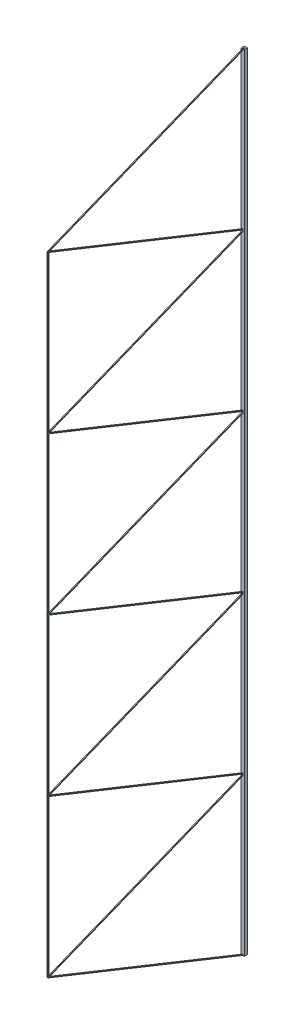
SolidWorks part; units mm, degrees
material "Alloy Steel (SS)"
ref_plane "Front Plane" through (0, 0, 0) normal (1, 0, 0) x (0, 1, 0)
ref_plane "Top Plane" through (0, 0, 0) normal (0, 0, 1) x (0, 1, 0)
ref_plane "Right Plane" through (0, 0, 0) normal (0, 1, 0) x (-1, 0, 0)
sketch "Sketch1" plane through (0, 0, 0) normal (1, 0, 0) x (0, 1, 0)
  line L0 (0, 0) -> (10000, 0)
  line L20 (9000, 2500) -> (7000, 2500)
  line L21 (7000, 2500) -> (5000, 2500)
  line L22 (5000, 2500) -> (3000, 2500)
  line L23 (3000, 2500) -> (1000, 2500)
  line L24 (0, 0) -> (1000, 2500)
  line L25 (9000, 2500) -> (10000, 0)
  line L26 (9000, 2500) -> (8000, 0)
  line L27 (8000, 0) -> (7000, 2500)
  line L28 (7000, 2500) -> (6000, 0)
  line L29 (6000, 0) -> (5000, 2500)
  line L30 (5000, 2500) -> (4000, 0)
  line L31 (4000, 0) -> (3000, 2500)
  line L32 (3000, 2500) -> (2000, 0)
  line L33 (2000, 0) -> (1000, 2500)
  point P3 (7728.8884, 2669.1518)
  point P16 (8313.1219, 4207.387)
  point P17 (1686.8781, 2500)
  dimension "D1" = 10000
  dimension "D2" = 2500
other "Hw5 SMALLBEAM40(1)"
ref_plane "Plane9" through (0, 0, 0) normal (0, 1, 0) x (0, 0, 1)
sketch "Sketch150" plane through (0, 0, 0) normal (0, 1, 0) x (0, 0, 1)
  line L0 (0, 20) -> (0, -20) construction
  line L1 (-20, -20) -> (20, -20)
  line L2 (-20, -20) -> (-20, 20)
  line L3 (-20, 20) -> (20, 20)
  line L4 (20, -20) -> (20, 20)
  point P6 (0, 0)
  point P7 (0, 0)
  dimension "D1" = 40
other "Hw5 SMALLBEAM10(1)"
ref_plane "Plane10" through (0, 0, 0) normal (0, 0.3714, 0.9285) x (0, -0.9285, 0.3714)
sketch "Sketch144" plane through (0, 0, 0) normal (0, 0.3714, 0.9285) x (0, -0.9285, 0.3714)
  line L0 (0, 5) -> (0, -5) construction
  line L1 (-5, -5) -> (5, -5)
  line L2 (-5, -5) -> (-5, 5)
  line L3 (-5, 5) -> (5, 5)
  line L4 (5, -5) -> (5, 5)
  point P6 (0, 0)
  point P7 (0, 0)
  dimension "D1" = 10
other "Hw5 SMALLBEAM10(2)"
ref_plane "Plane11" through (0, 2000, 0) normal (0, -0.3714, 0.9285) x (0, -0.9285, -0.3714)
sketch "Sketch147" plane through (0, 2000, 0) normal (0, -0.3714, 0.9285) x (0, -0.9285, -0.3714)
  line L0 (0, 5) -> (0, -5) construction
  line L1 (-5, -5) -> (5, -5)
  line L2 (-5, -5) -> (-5, 5)
  line L3 (-5, 5) -> (5, 5)
  line L4 (5, -5) -> (5, 5)
  point P6 (0, 0)
  point P7 (0, 0)
  dimension "D1" = 10
